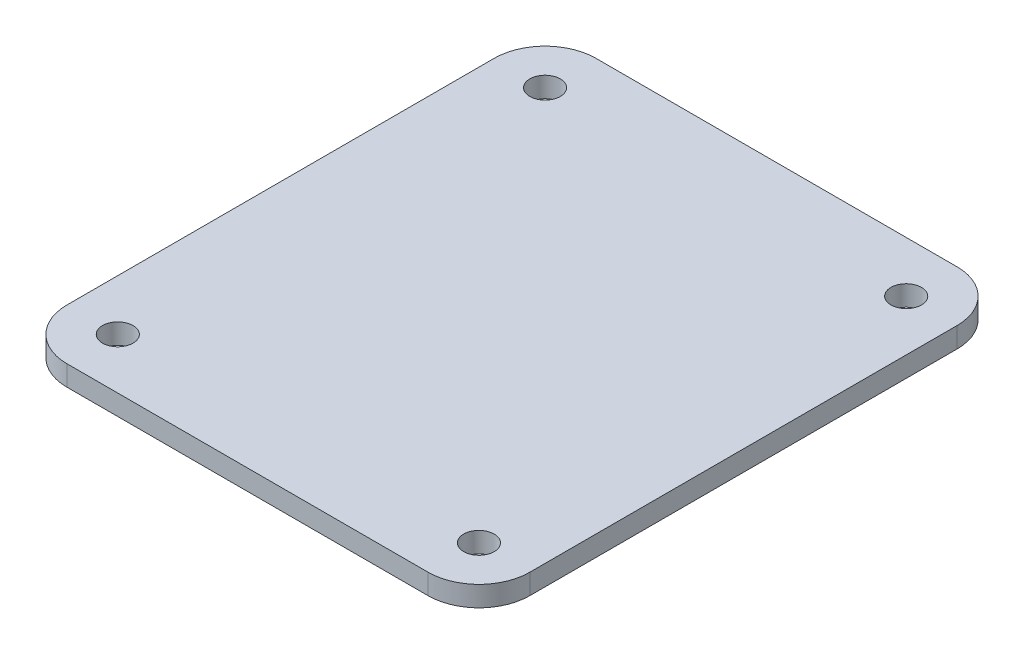
SolidWorks part; units mm, degrees
ref_plane "前基準面" through (0, 0, 0) normal (0, 0, 1) x (1, 0, 0)
ref_plane "上基準面" through (0, 0, 0) normal (0, 1, 0) x (1, 0, 0)
ref_plane "右基準面" through (0, 0, 0) normal (1, 0, 0) x (0, 0, -1)
sketch "草圖1" plane through (0, 0, 0) normal (0, 1, 0) x (1, 0, 0)
  line L0 (-17.75, 26) -> (17.75, 26)
  line L1 (-17.75, 21) -> (17.75, 21) construction
  line L2 (-17.75, 21) -> (-17.75, -21) construction
  line L3 (-17.75, -21) -> (17.75, -21) construction
  line L4 (17.75, 21) -> (17.75, -21) construction
  line L5 (-17.75, 21) -> (17.75, -21) construction
  line L6 (-17.75, -21) -> (17.75, 21) construction
  line L7 (22.75, 21) -> (22.75, -21)
  line L8 (-17.75, -26) -> (17.75, -26)
  line L9 (-22.75, 21) -> (-22.75, -21)
  line L10 (-22.75, -26) -> (22.75, -26) construction
  line L11 (-22.75, 26) -> (-22.75, -26) construction
  line L12 (22.75, 26) -> (22.75, -26) construction
  line L13 (-22.75, 26) -> (22.75, 26) construction
  circle A0 centre (17.75, 21) radius 1.5
  circle A1 centre (-17.75, 21) radius 1.5
  circle A2 centre (-17.75, -21) radius 1.5
  circle A3 centre (17.75, -21) radius 1.5
  arc A4 (-17.75, -26) -> (-22.75, -21) centre (-17.75, -21) cw
  arc A5 (22.75, -21) -> (17.75, -26) centre (17.75, -21) cw
  arc A6 (17.75, 26) -> (22.75, 21) centre (17.75, 21) cw
  arc A7 (-17.75, 26) -> (-22.75, 21) centre (-17.75, 21) ccw
  point P0 (0, 0)
  dimension "D3" = 3
  dimension "D5" = 5
  dimension "D1" = 35.5
  dimension "D2" = 42
  dimension "D4" = 5
extrude "填料-伸長1" add sketch "草圖1" along normal blind 2
